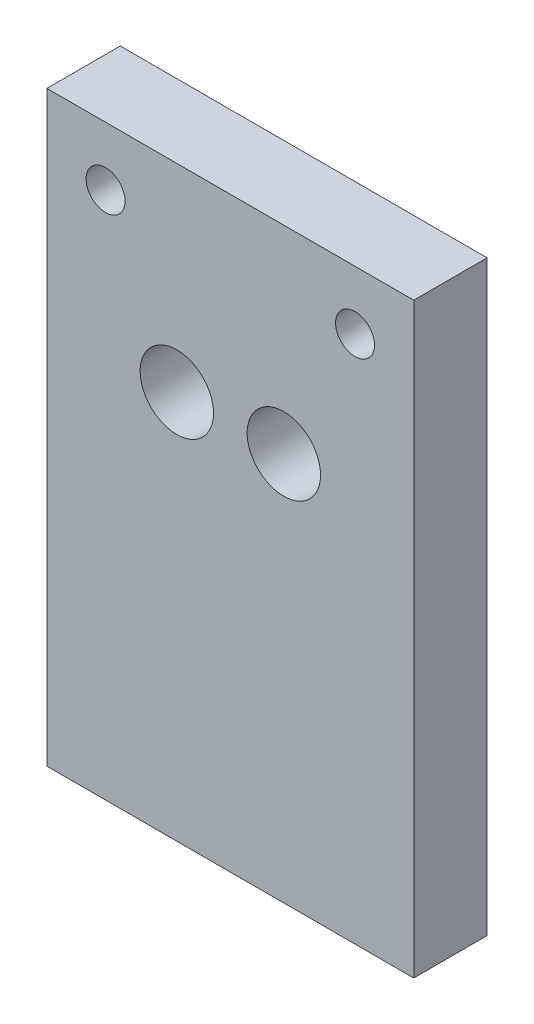
SolidWorks part; units mm, degrees
material "Acrylic (Medium-high impact)"
ref_plane "Front Plane" through (0, 0, 0) normal (0, 0, 1) x (1, 0, 0)
ref_plane "Top Plane" through (0, 0, 0) normal (0, 1, 0) x (1, 0, 0)
ref_plane "Right Plane" through (0, 0, 0) normal (1, 0, 0) x (0, 0, -1)
sketch "Sketch1" plane through (0, 0, 0) normal (0, 0, 1) x (1, 0, 0)
  line L1 (-31.75, 67.31) -> (31.75, 67.31)
  line L2 (-31.75, 67.31) -> (-31.75, -67.31)
  line L3 (-31.75, -67.31) -> (31.75, -67.31)
  line L4 (31.75, 67.31) -> (31.75, -67.31)
  line L5 (-31.75, 67.31) -> (31.75, -67.31) construction
  line L6 (-31.75, -67.31) -> (31.75, 67.31) construction
  circle A0 centre (-9.2608, 0) radius 6.35
  circle A1 centre (9.2608, 0) radius 6.35
  point P0 (0, 0)
  dimension "D3" = 12.7
  dimension "D4" = 12.7
  dimension "D1" = 63.5
  dimension "D2" = 134.62
  dimension "D5" = 9.2608
  dimension "D6" = 9.2608
extrude "Boss-Extrude1" add sketch "Sketch1" along normal blind 12.7
sketch "Sketch2" plane through (0, 0, 12.7) normal (0, 0, 1) x (1, 0, 0)
  line L0 (31.75, -67.31) -> (31.75, 67.31) construction
  line L1 (-31.75, 67.31) -> (31.75, 67.31)
  line L2 (-31.75, 67.31) -> (-31.75, 34.29)
  line L3 (-31.75, 34.29) -> (31.75, 34.29)
  line L4 (31.75, 67.31) -> (31.75, 34.29)
  dimension "D1" = 33.02
extrude "Cut-Extrude1" cut sketch "Sketch2" against normal through all
sketch "Sketch3" plane through (0, 0, 12.7) normal (0, 0, 1) x (1, 0, 0)
  line L0 (-9.2608, 0) -> (-9.2608, -83.7414) construction
hole_wizard "1/4 Clearance Hole1" positions "Sketch6" profile "Sketch5" hole size "1/4" standard "ANSI Inch" end condition through all
sketch "Sketch6" plane through (0, 0, 12.7) normal (0, 0, 1) x (1, 0, 0)
  line L0 (-31.75, 34.29) -> (31.75, 34.29) construction
  line L1 (-31.75, 34.29) -> (-31.75, -67.31) construction
  point P0 (-21.59, 24.13)
  dimension "D1" = 10.16
  dimension "D2" = 10.16
sketch "Sketch5" plane through (-21.59, 24.13, 12.7) normal (1, 0, 0) x (0, -1, 0)
  line L0 (0, 0) -> (0, 12.7)
  line L1 (0, 12.7) -> (3.3782, 12.7)
  line L2 (3.3782, 12.7) -> (3.3782, 0)
  line L5 (3.3782, 0) -> (0, 0)
  line L11 (0, -6.35) -> (0, 107.95) construction
  dimension "Thru Hole Dia." = 6.7564
  dimension "Thru Hole Depth" = 12.7
mirror "Mirror1" about plane through (0, 0, 0) normal (1, 0, 0) of "1/4 Clearance Hole1"
hole_wizard "#10-32 Tapped Hole1" positions "Sketch7" profile "Sketch8" tap size "#10-32" standard "ANSI Inch"
sketch "Sketch7" plane through (0, -67.31, 0) normal (0, -1, 0) x (-1, 0, 0)
  line L0 (31.75, -12.7) -> (-31.75, -12.7) construction
  line L1 (31.75, -12.7) -> (31.75, 0) construction
  point P0 (21.59, -6.35)
  point P9 (17.8641, -9.1288)
  point P10 (0, 0)
  dimension "D1" = 6.35
  dimension "D2" = 10.16
sketch "Sketch8" plane through (-21.59, -67.31, 6.35) normal (1, 0, 0) x (0, 0, -1)
  line L0 (0, 0) -> (0, 26.6133)
  line L1 (0, 26.6133) -> (2.0193, 25.4)
  line L2 (2.0193, 25.4) -> (2.0193, 0)
  line L5 (2.0193, 0) -> (0, 0)
  line L10 (0, 26.6133) -> (-2.0193, 25.4) construction
  line L11 (0, -6.35) -> (0, 107.95) construction
  dimension "Tap Drill Dia." = 4.0386
  dimension "Tap Drill Depth" = 25.4
  dimension "Drill Angle" = 118
cosmetic thread "Hole Thread1" parameters "D1"=9.652, "D2"=4.826
mirror "Mirror2" about plane through (0, 0, 0) normal (1, 0, 0) of "#10-32 Tapped Hole1"
